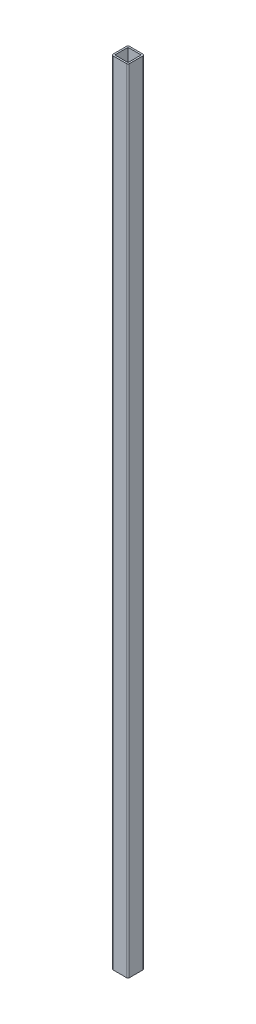
SolidWorks part; units mm, degrees
ref_plane "Front Plane" through (0, 0, 0) normal (0, 0, 1) x (1, 0, 0)
ref_plane "Top Plane" through (0, 0, 0) normal (0, 1, 0) x (1, 0, 0)
ref_plane "Right Plane" through (0, 0, 0) normal (1, 0, 0) x (0, 0, -1)
sketch "Sketch4" plane through (0, 0, 0) normal (0, 1, 0) x (1, 0, 0)
  line L0 (10.16, 10.16) -> (10.16, -10.16)
  line L1 (12.7, 12.7) -> (-12.7, 12.7)
  line L2 (12.7, 12.7) -> (12.7, -12.7)
  line L3 (12.7, -12.7) -> (-12.7, -12.7)
  line L4 (-12.7, 12.7) -> (-12.7, -12.7)
  line L5 (10.16, -10.16) -> (-10.16, -10.16)
  line L6 (-10.16, 10.16) -> (-10.16, -10.16)
  line L7 (10.16, 10.16) -> (-10.16, 10.16)
  point P0 (0, 0)
  dimension "D1" = 25.4
  dimension "D2" = 25.4
  dimension "D3" = 2.54
extrude "Boss-Extrude6" add sketch "Sketch4" along normal blind 1219.2 contours L4 L3 L2 L1
shell "Shell1" thickness 2.54
fillet "Fillet1" radius 2.54 4 edges at (-12.7, 609.6, 12.7) (12.7, 609.6, 12.7) (12.7, 609.6, -12.7) (-12.7, 609.6, -12.7)
